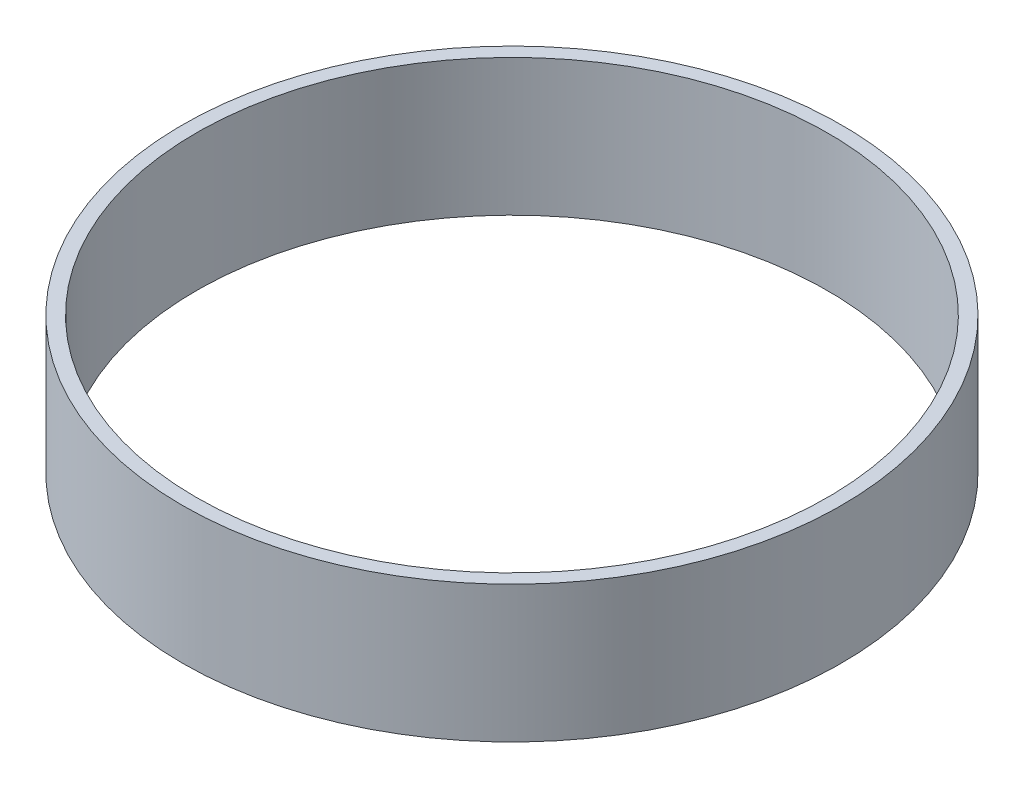
SolidWorks part; units mm, degrees
material "PTFE (general)"
ref_plane "Front Plane" through (0, 0, 0) normal (0, 0, 1) x (1, 0, 0)
ref_plane "Top Plane" through (0, 0, 0) normal (0, 1, 0) x (1, 0, 0)
ref_plane "Right Plane" through (0, 0, 0) normal (1, 0, 0) x (0, 0, -1)
sketch "Sketch1" plane through (0, 0, 0) normal (0, 1, 0) x (0.9995, 0, 0.031)
  circle A0 centre (-29.3916, -2.6114) radius 24.116
  circle A1 centre (-29.3916, -2.6114) radius 23.1
  dimension "D1" = 46.2
  dimension "D2" = 1.016
extrude "Boss-Extrude1" add sketch "Sketch1" along normal blind 10
